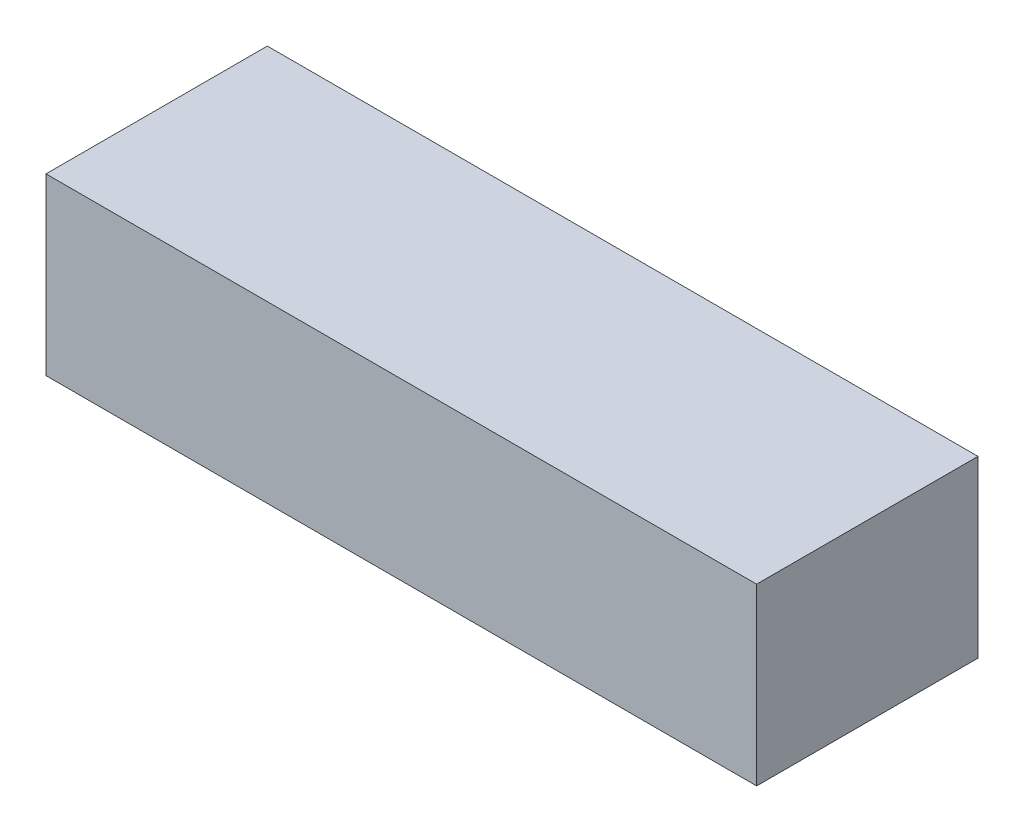
SolidWorks part; units mm, degrees
ref_plane "Front Plane" through (0, 0, 0) normal (0, 0, 1) x (1, 0, 0)
ref_plane "Top Plane" through (0, 0, 0) normal (0, 1, 0) x (1, 0, 0)
ref_plane "Right Plane" through (0, 0, 0) normal (1, 0, 0) x (0, 0, -1)
sketch "Sketch1" plane through (0, 0, 0) normal (1, 0, 0) x (0, 0, -1)
  line L1 (-9.5, 7.5) -> (9.5, 7.5)
  line L2 (-9.5, 7.5) -> (-9.5, -7.5)
  line L3 (-9.5, -7.5) -> (9.5, -7.5)
  line L4 (9.5, 7.5) -> (9.5, -7.5)
  line L5 (-9.5, 7.5) -> (9.5, -7.5) construction
  line L6 (-9.5, -7.5) -> (9.5, 7.5) construction
  point P0 (0, 0)
  dimension "D1" = 15
  dimension "D2" = 19
extrude "Boss-Extrude1" add sketch "Sketch1" along normal blind 61
